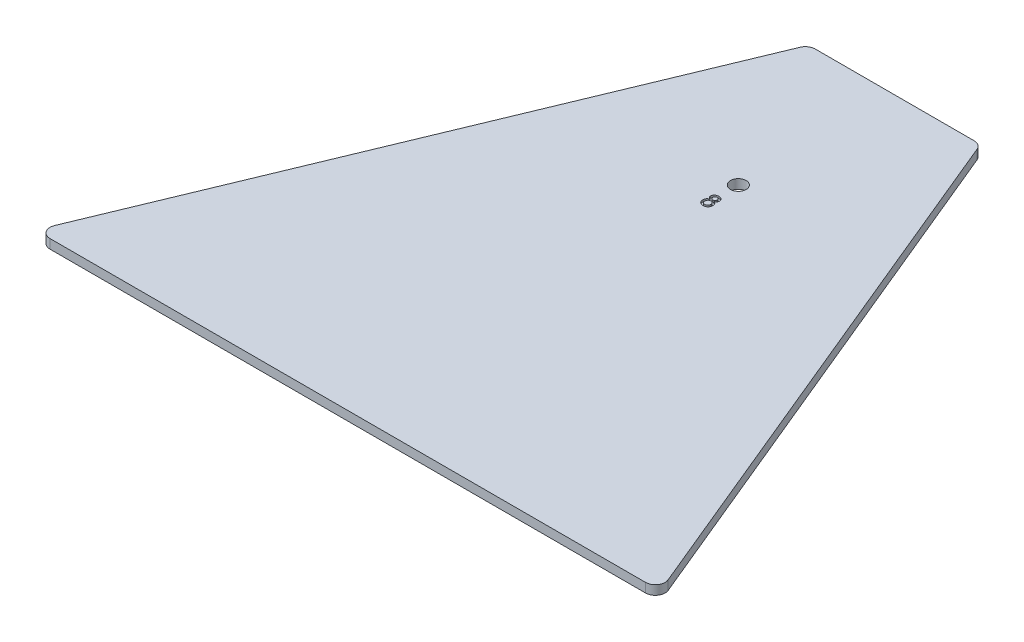
SolidWorks part; units mm, degrees
material "Acrylic (Medium-high impact)"
ref_plane "Front Plane" through (0, 0, 0) normal (0, 0, 1) x (1, 0, 0)
ref_plane "Top Plane" through (0, 0, 0) normal (0, 1, 0) x (1, 0, 0)
ref_plane "Right Plane" through (0, 0, 0) normal (1, 0, 0) x (0, 0, -1)
sketch "Sketch1" plane through (0, 0, 0) normal (0, 1, 0) x (1, 0, 0)
  line L0 (-4.445, 0) -> (-4.445, -355.6) construction
  line L1 (-60.325, 0) -> (51.435, 0)
  line L2 (51.435, 0) -> (198.7293, -355.6)
  line L3 (198.7293, -355.6) -> (-207.6193, -355.6)
  line L4 (-60.325, 0) -> (-207.6193, -355.6)
  dimension "D1" = 355.6
  dimension "D2" = 45
  dimension "D3" = 111.76
extrude "Boss-Extrude1" add sketch "Sketch1" along normal blind 5.9944
sketch "Sketch2" plane through (0, 5.9944, 0) normal (0, 1, 0) x (1, 0, 0)
  line L0 (-4.445, 0) -> (-4.445, -101.6) construction
  line L1 (51.435, 0) -> (-60.325, 0) construction
  circle A0 centre (-4.445, -101.6) radius 5.08
  dimension "D1" = 10.16
  dimension "D2" = 101.6
extrude "Cut-Extrude1" cut sketch "Sketch2" against normal through all
sketch "Sketch3" plane through (0, 5.9944, 0) normal (0, 1, 0) x (1, 0, 0)
  line L0 (-4.445, -101.6) -> (-4.445, -114.3) construction
  line L1 (-8.255, -124.46) -> (-0.635, -124.46) construction
  line L2 (-8.255, -124.46) -> (-8.255, -114.3) construction
  line L3 (-8.255, -114.3) -> (-0.635, -114.3) construction
  line L4 (-0.635, -124.46) -> (-0.635, -114.3) construction
  circle A0 centre (-4.445, -101.6) radius 5.08 construction
  text T0 "8" font "Cordia New" height 10.16
  dimension "D1" = 7.62
  dimension "D2" = 10.16
  dimension "D3" = 12.7
extrude "Cut-Extrude2" cut sketch "Sketch3" against normal blind 1.27
fillet "Fillet1" radius 6.35 4 edges at (198.7293, 2.9972, 355.6) (-207.6193, 2.9972, 355.6) (51.435, 2.9972, 0) (-60.325, 2.9972, 0)
